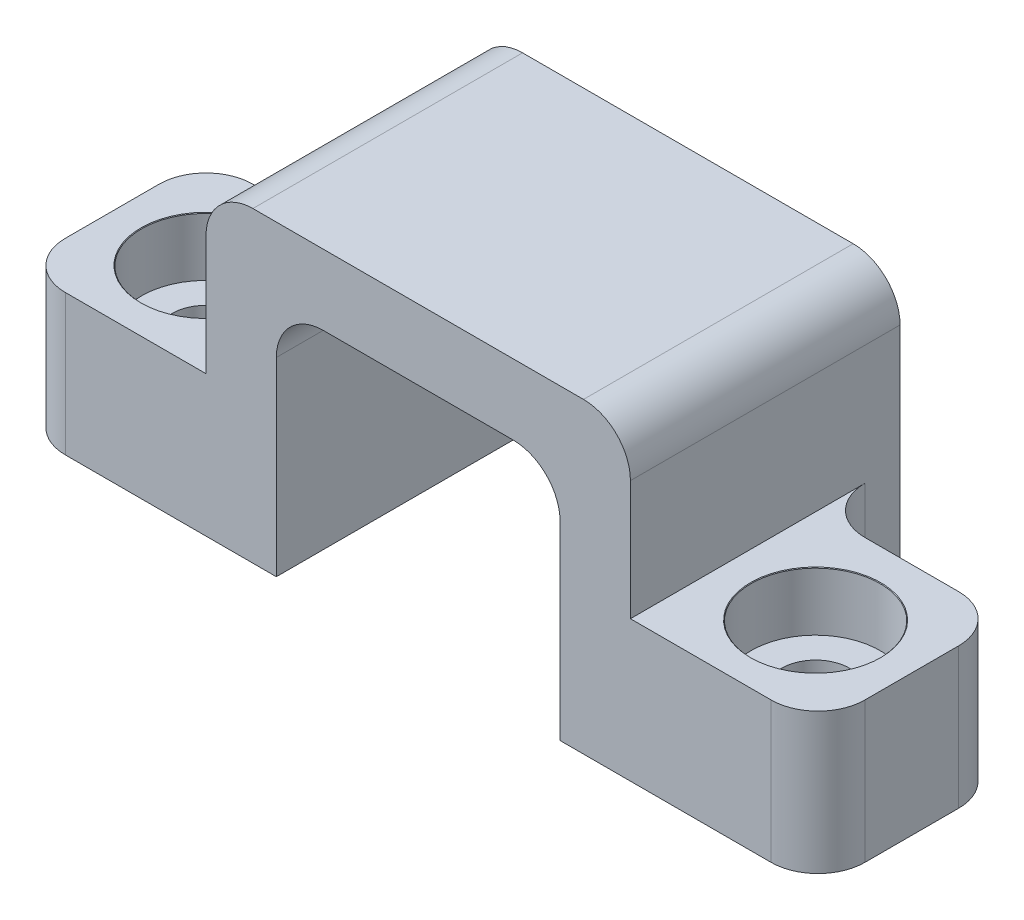
SolidWorks part; units mm, degrees
material "ABS"
ref_plane "Front Plane" through (0, 0, 0) normal (0, 0, 1) x (1, 0, 0)
ref_plane "Top Plane" through (0, 0, 0) normal (0, 1, 0) x (1, 0, 0)
ref_plane "Right Plane" through (0, 0, 0) normal (1, 0, 0) x (0, 0, -1)
sketch "Sketch1" plane through (0, 0, 0) normal (0, 0, 1) x (1, 0, 0)
  line L0 (-9.05, 0) -> (-6.05, 0)
  line L1 (-6.05, 0) -> (-6.05, 10.1)
  line L2 (-6.05, 10.1) -> (6.05, 10.1)
  line L3 (6.05, 10.1) -> (6.05, 0)
  line L4 (6.05, 0) -> (9.05, 0)
  line L5 (9.05, 0) -> (9.05, 13.1)
  line L6 (9.05, 13.1) -> (-9.05, 13.1)
  line L7 (-9.05, 13.1) -> (-9.05, 0)
  line L8 (0, 2.0828) -> (0, -1.5478) construction
  dimension "D1" = 3
  dimension "D2" = 3
  dimension "D3" = 10.1
  dimension "D4" = 12.1
extrude "Boss-Extrude1" add sketch "Sketch1" along normal blind 11.5
sketch "Sketch2" plane through (0, 0, 11.5) normal (0, 0, 1) x (1, 0, 0)
  line L1 (-9.05, 0) -> (-17.05, 0)
  line L2 (-9.05, 0) -> (-9.05, 6)
  line L3 (-9.05, 6) -> (-17.05, 6)
  line L4 (-17.05, 0) -> (-17.05, 6)
  line L5 (9.05, 0) -> (17.05, 0)
  line L6 (9.05, 0) -> (9.05, 6)
  line L7 (9.05, 6) -> (17.05, 6)
  line L8 (17.05, 0) -> (17.05, 6)
  dimension "D1" = 8
extrude "Boss-Extrude2" add sketch "Sketch2" against normal blind 8
sketch "Sketch3" plane through (0, 6, 0) normal (0, 1, 0) x (1, 0, 0)
sketch "Sketch5" plane through (0, 6, 0) normal (0, 1, 0) x (1, 0, 0)
  line L0 (-13.05, -3.9674) -> (-13.05, -10.9231) construction
  line L2 (13.05, -3.9674) -> (13.05, -10.9231) construction
  line L4 (9.05, -3.5) -> (9.05, -11.5) construction
  line L5 (17.05, -3.5) -> (17.05, -11.5) construction
  line L6 (-9.05, -11.5) -> (-9.05, 0) construction
  line L7 (-17.05, -3.5) -> (-17.05, -11.5) construction
  line L8 (-16.2184, -7.5) -> (-10.0317, -7.5) construction
  line L10 (-9.05, -3.5) -> (-17.05, -3.5) construction
  line L11 (-9.05, -11.5) -> (-17.05, -11.5) construction
  point P0 (-13.05, -7.5)
  point P2 (13.05, -7.6025)
  point P28 (0, 0)
hole_wizard "CBORE for M2.5 SHCS1" positions "Sketch5" profile "Sketch4" counterbore size "M2.5" standard "ANSI Metric" end condition through all
sketch "Sketch4" plane through (-13.05, 6, 7.5) normal (1, 0, 0) x (0, 0, 1)
  line L0 (0, 0) -> (0, 6)
  line L1 (0, 6) -> (1.45, 6)
  line L3 (1.45, 6) -> (1.45, 2.5)
  line L4 (2.75, 2.5) -> (1.45, 2.5)
  line L5 (2.75, 2.5) -> (2.75, 0.025)
  line L6 (2.75, 0.025) -> (2.775, 0)
  line L7 (2.775, 0) -> (0, 0)
  line L8 (-2.75, 0.025) -> (-2.775, 0) construction
  line L11 (0, -6.35) -> (0, 107.95) construction
  dimension "Thru Hole Dia." = 2.9
  dimension "Thru Hole Depth" = 6
  dimension "C'Bore Dia." = 5.5
  dimension "C'Bore Depth" = 2.5
  dimension "Near C'Sink Dia." = 5.55
  dimension "Near C'Sink Angle" = 90
fillet "Fillet2" radius 2 10 edges at (17.05, 3, 11.5) (17.05, 3, 3.5) (9.05, 3, 3.5) (6.05, 10.1, 5.75) (-6.05, 10.1, 5.75) (-9.05, 3, 3.5) (-17.05, 3, 3.5) (-17.05, 3, 11.5) (9.05, 13.1, 5.75) (-9.05, 13.1, 5.75)
